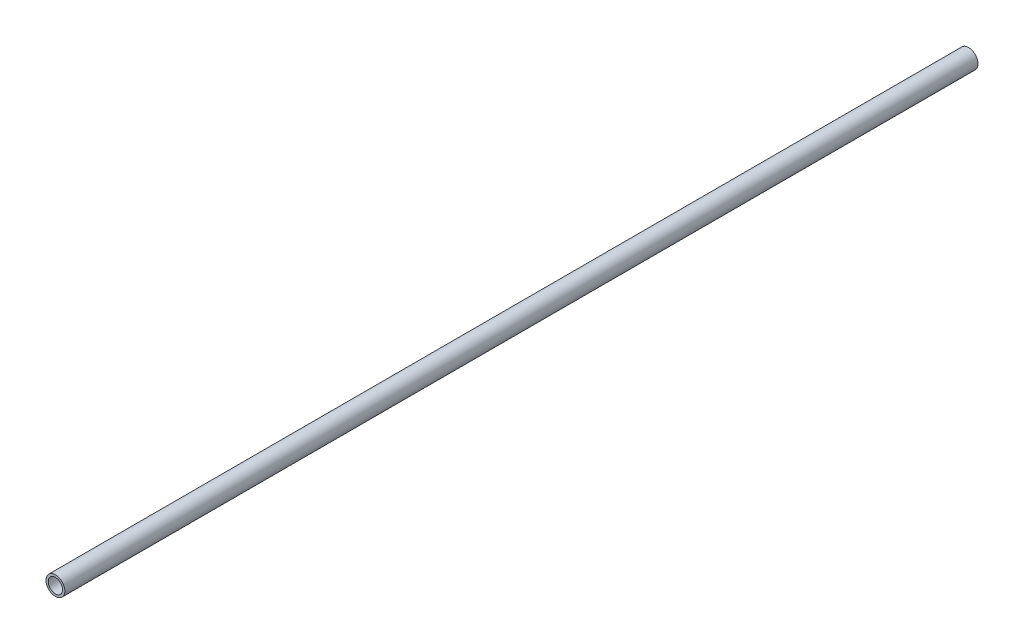
SolidWorks part; units mm, degrees
material "Plain Carbon Steel"
ref_plane "Front Plane" through (0, 0, 0) normal (0, 0, 1) x (1, 0, 0)
ref_plane "Top Plane" through (0, 0, 0) normal (0, 1, 0) x (1, 0, 0)
ref_plane "Right Plane" through (0, 0, 0) normal (1, 0, 0) x (0, 0, -1)
sketch "Sketch1" plane through (0, 0, 0) normal (0, 0, 1) x (1, 0, 0)
  circle A0 centre (0, 0) radius 12.7
  circle A1 centre (0, 0) radius 16.7005
extrude "Boss-Extrude1" add sketch "Sketch1" along normal blind 1618.996
